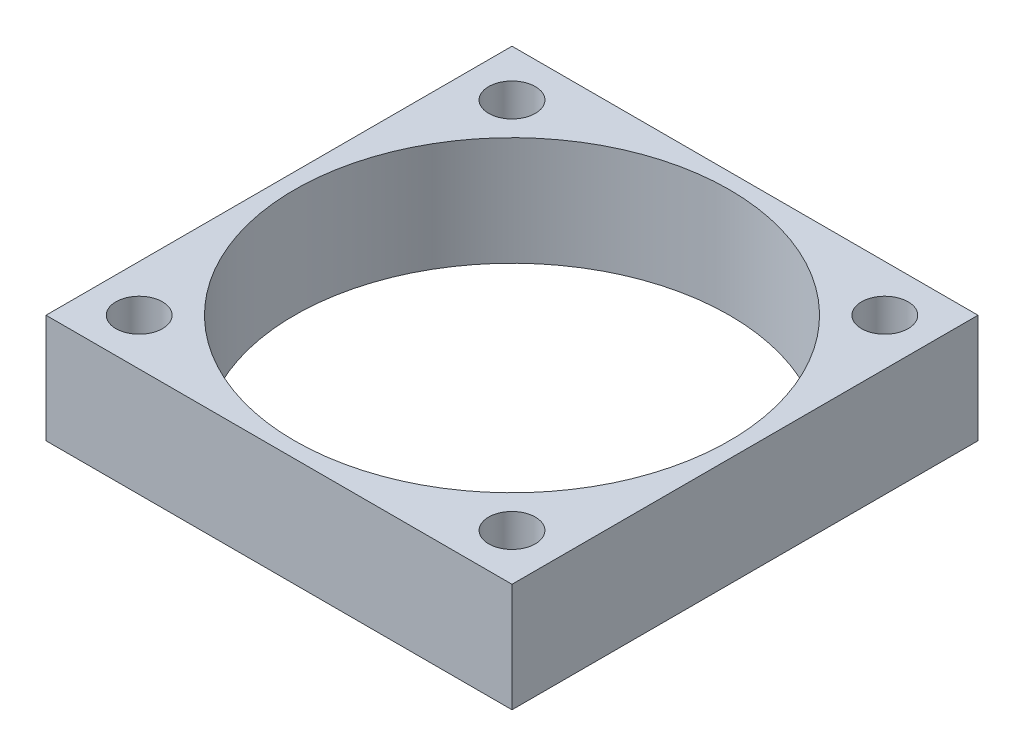
SolidWorks part; units mm, degrees
ref_plane "前视基准面" through (0, 0, 0) normal (0, 0, 1) x (1, 0, 0)
ref_plane "上视基准面" through (0, 0, 0) normal (0, 1, 0) x (1, 0, 0)
ref_plane "右视基准面" through (0, 0, 0) normal (1, 0, 0) x (0, 0, -1)
sketch "草图1" plane through (0, 0, 0) normal (0, 1, 0) x (1, 0, 0)
  line L0 (1.16, 15.76) -> (1.16, -14.24) construction
  line L1 (-13.84, 15.76) -> (16.16, 15.76)
  line L2 (-13.84, 15.76) -> (-13.84, -14.24)
  line L3 (-13.84, -14.24) -> (16.16, -14.24)
  line L4 (16.16, 15.76) -> (16.16, -14.24)
  line L5 (-13.84, 0.76) -> (16.16, 0.76) construction
  circle A0 centre (-10.84, 12.76) radius 1.5
  circle A1 centre (-10.84, -11.24) radius 1.5
  circle A2 centre (13.16, -11.24) radius 1.5
  circle A3 centre (13.16, 12.76) radius 1.5
  circle A4 centre (1.16, 0.76) radius 14
  point P10 (1.16, 0.76)
  dimension "D6" = 3
  dimension "D7" = 28
  dimension "D1" = 30
  dimension "D2" = 30
  dimension "D3" = 12
  dimension "D4" = 12
  dimension "D5" = 4
extrude "凸台-拉伸1" add sketch "草图1" along normal blind 7
